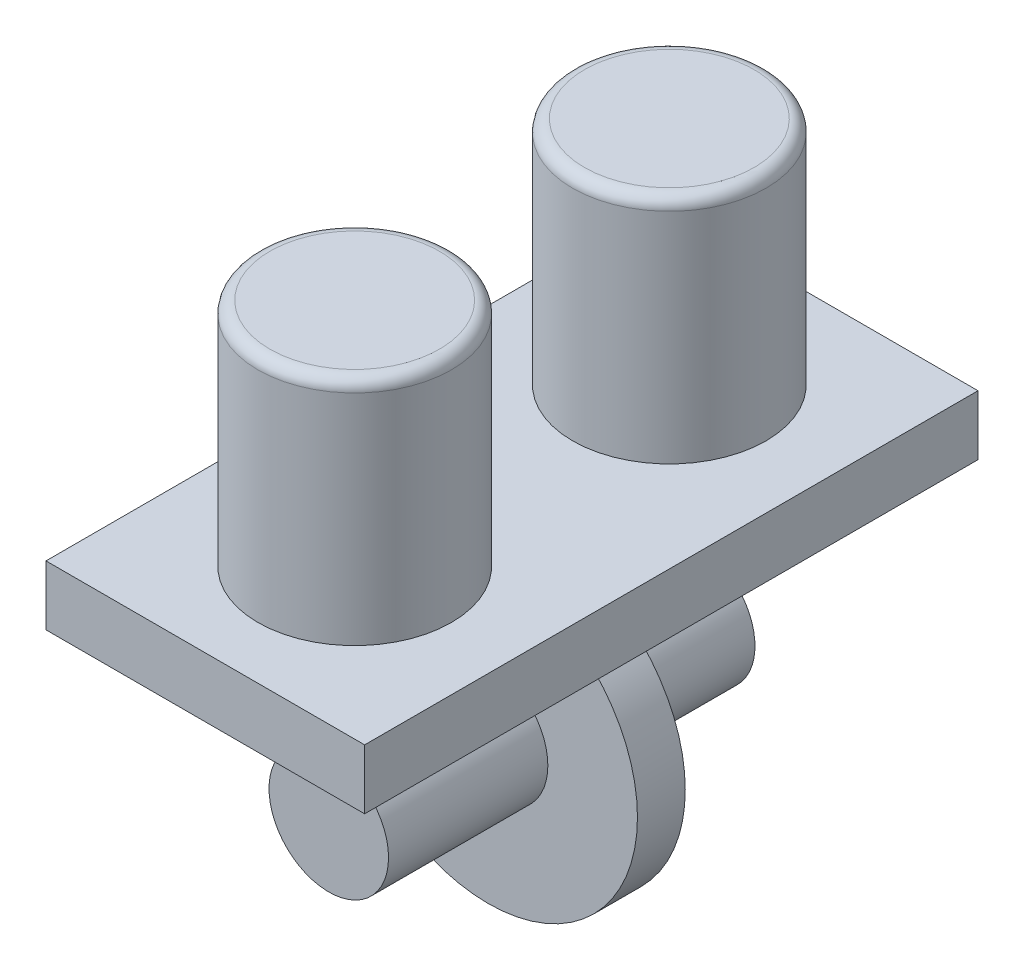
SolidWorks part; units mm, degrees
ref_plane "Front Plane" through (0, 0, 0) normal (0, 0, 1) x (1, 0, 0)
ref_plane "Top Plane" through (0, 0, 0) normal (0, 1, 0) x (1, 0, 0)
ref_plane "Right Plane" through (0, 0, 0) normal (1, 0, 0) x (0, 0, -1)
sketch "Sketch1" plane through (0, 0, 0) normal (0, 0, 1) x (1, 0, 0)
  line L0 (-101.6, 95.25) -> (-50.8, 95.25)
  line L1 (-101.6, 133.35) -> (101.6, 133.35)
  line L2 (-101.6, 133.35) -> (-101.6, 95.25)
  line L3 (-101.6, 95.25) -> (101.6, 95.25)
  line L4 (101.6, 133.35) -> (101.6, 95.25)
  line L5 (101.6, 95.25) -> (50.8, 95.25)
  line L6 (-50.8, 95.25) -> (0, 95.25)
  circle A0 centre (0, 0) radius 95.25
  arc A1 (-50.8, 95.25) -> (-51.3042, 80.2524) centre (-57.1203, 87.9552) cw
  arc A2 (50.8, 95.25) -> (50.9196, 80.497) centre (57.0841, 87.9239) ccw
  dimension "D5" = 50.8
  dimension "D7" = 9.652
  dimension "D8" = 9.652
  dimension "D1" = 203.2
  dimension "D2" = 38.1
  dimension "D3" = 101.6
  dimension "D4" = 95.25
  dimension "D6" = 50.8
extrude "Boss-Extrude1" add sketch "Sketch1" along normal blind 30.48 contours A0 | L2 L1 L4 L3
sketch "Sketch4" plane through (0, 0, 0) normal (0, 0, -1) x (-1, 0, 0)
  line L1 (-101.6, 133.35) -> (101.6, 133.35)
  line L2 (-101.6, 133.35) -> (-101.6, 95.25)
  line L3 (-101.6, 95.25) -> (101.6, 95.25)
  line L4 (101.6, 133.35) -> (101.6, 95.25)
extrude "Boss-Extrude2" add sketch "Sketch4" along normal blind 180.34
sketch "Sketch5" plane through (0, 0, 30.48) normal (0, 0, 1) x (1, 0, 0)
  line L1 (-101.6, 133.35) -> (101.6, 133.35)
  line L2 (-101.6, 133.35) -> (-101.6, 95.25)
  line L3 (-101.6, 95.25) -> (101.6, 95.25)
  line L4 (101.6, 133.35) -> (101.6, 95.25)
extrude "Boss-Extrude3" add sketch "Sketch5" along normal blind 180.34
sketch "Sketch6" plane through (0, 0, 30.48) normal (0, 0, 1) x (1, 0, 0)
  circle A2 centre (0, 0) radius 38.1
  dimension "D1" = 76.2
extrude "Boss-Extrude4" add sketch "Sketch6" along normal blind 101.6
sketch "Sketch7" plane through (0, 0, 0) normal (0, 0, -1) x (-1, 0, 0)
  circle A0 centre (0, 0) radius 38.1
  dimension "D1" = 76.2
extrude "Boss-Extrude5" add sketch "Sketch7" along normal blind 101.6
sketch "Sketch8" plane through (0, 133.35, 0) normal (0, 1, 0) x (1, 0, 0)
  line L0 (101.6, -210.82) -> (101.6, 180.34) construction
  line L1 (101.6, -210.82) -> (-101.6, -210.82) construction
  line L2 (-101.6, 180.34) -> (101.6, 180.34) construction
  circle A0 centre (0, -115.57) radius 61.722
  circle A1 centre (0, 85.09) radius 61.722
  dimension "D1" = 123.444
  dimension "D5" = 200.66
  dimension "D2" = 101.6
  dimension "D3" = 95.25
  dimension "D6" = 95.25
  dimension "D4" = 2
extrude "Boss-Extrude6" add sketch "Sketch8" along normal blind 147.1422
fillet "Fillet1" radius 7.62 2 edges at (0, 280.4922, 177.292) (0, 280.4922, -23.368)
